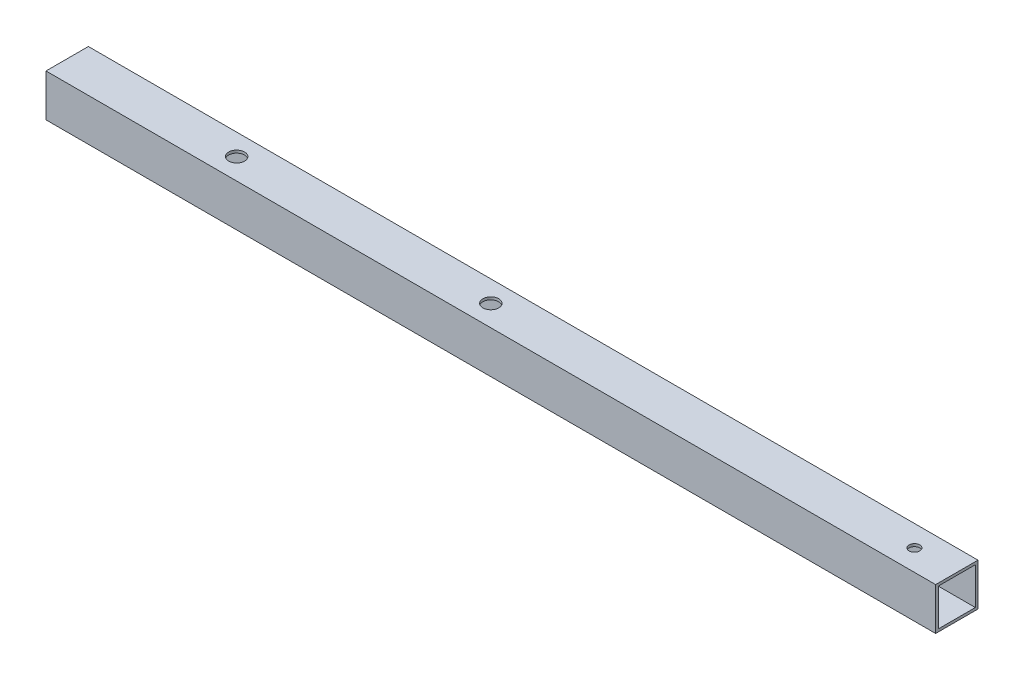
SolidWorks part; units mm, degrees
ref_plane "Front Plane" through (0, 0, 0) normal (0, 0, 1) x (1, 0, 0)
ref_plane "Top Plane" through (0, 0, 0) normal (0, 1, 0) x (1, 0, 0)
ref_plane "Right Plane" through (0, 0, 0) normal (1, 0, 0) x (0, 0, -1)
sketch "Sketch1" plane through (0, 0, 0) normal (1, 0, 0) x (0, 0, -1)
  line L1 (-11.1125, -11.1125) -> (11.1125, -11.1125)
  line L2 (-11.1125, -11.1125) -> (-11.1125, 11.1125)
  line L3 (-11.1125, 11.1125) -> (11.1125, 11.1125)
  line L4 (11.1125, -11.1125) -> (11.1125, 11.1125)
  line L5 (-11.1125, -11.1125) -> (11.1125, 11.1125) construction
  line L6 (-11.1125, 11.1125) -> (11.1125, -11.1125) construction
  line L7 (-12.7, -12.7) -> (12.7, -12.7)
  line L8 (-12.7, -12.7) -> (-12.7, 12.7)
  line L9 (-12.7, 12.7) -> (12.7, 12.7)
  line L10 (12.7, -12.7) -> (12.7, 12.7)
  line L11 (-12.7, -12.7) -> (12.7, 12.7) construction
  line L12 (-12.7, 12.7) -> (12.7, -12.7) construction
  point P0 (0, 0)
  point P6 (0, 0)
  dimension "D1" = 25.4
  dimension "D2" = 1.5875
extrude "Boss-Extrude1" add sketch "Sketch1" along normal blind 533.4
sketch "Sketch2" plane through (0, 12.7, 0) normal (0, 1, 0) x (1, 0, 0)
  circle A0 centre (101.6, 0) radius 4.7625
  circle A1 centre (254, 0) radius 4.7625
  dimension "D1" = 9.525
  dimension "D2" = 101.6
  dimension "D3" = 152.4
extrude "Cut-Extrude1" cut sketch "Sketch2" against normal through all
sketch "Sketch3" plane through (0, 12.7, 0) normal (0, 1, 0) x (1, 0, 0)
  circle A0 centre (508, 0) radius 3.175
  circle A1 centre (101.6, 0) radius 4.7625 construction
  dimension "D1" = 6.35
  dimension "D2" = 406.4
extrude "Cut-Extrude2" cut sketch "Sketch3" against normal through all
